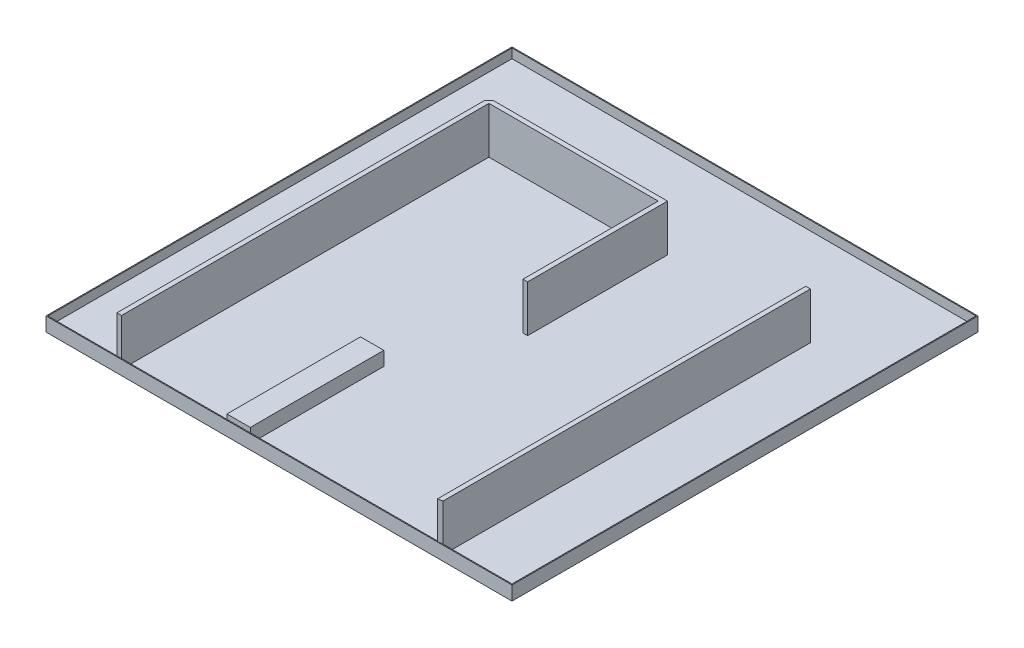
SolidWorks part; units mm, degrees
ref_plane "Front Plane" through (0, 0, 0) normal (0, 0, 1) x (1, 0, 0)
ref_plane "Top Plane" through (0, 0, 0) normal (0, 1, 0) x (1, 0, 0)
ref_plane "Right Plane" through (0, 0, 0) normal (1, 0, 0) x (0, 0, -1)
sketch "Sketch1" plane through (0, 0, 0) normal (0, 1, 0) x (1, 0, 0)
  line L1 (-5000, -5000) -> (5000, -5000)
  line L2 (-5000, -5000) -> (-5000, 5000)
  line L3 (-5000, 5000) -> (5000, 5000)
  line L4 (5000, -5000) -> (5000, 5000)
  line L5 (0, 5000) -> (0, -5000) construction
  line L6 (-5000, 0) -> (5000, 0) construction
  point P0 (0, 0)
  dimension "D1" = 10000
  dimension "D2" = 10000
extrude "Boss-Extrude1" add sketch "Sketch1" along normal blind 100
sketch "Sketch2" plane through (0, 100, 0) normal (0, 1, 0) x (1, 0, 0)
  line L1 (-5000, -5000) -> (5000, -5000)
  line L2 (-5000, -5000) -> (-5000, 5000)
  line L3 (-5000, 5000) -> (5000, 5000)
  line L4 (5000, -5000) -> (5000, 5000)
  line L5 (0, 5000) -> (0, -5000) construction
  line L6 (-5000, 0) -> (5000, 0) construction
  line L7 (-4980, -4980) -> (4980, -4980)
  line L8 (-4980, -4980) -> (-4980, 4980)
  line L9 (-4980, 4980) -> (4980, 4980)
  line L10 (4980, -4980) -> (4980, 4980)
  line L11 (0, 4980) -> (0, -4980) construction
  line L12 (-4980, 0) -> (4980, 0) construction
  point P0 (0, 0)
  point P4 (0, 0)
  dimension "D1" = 9960
  dimension "D2" = 9960
extrude "Boss-Extrude2" add sketch "Sketch2" along normal blind 200
sketch "Sketch5" plane through (0, 100, 0) normal (0, 1, 0) x (1, 0, 0)
  line L0 (3500, -4980) -> (3500, 2903.0481)
  line L1 (-4980, -4980) -> (4980, -4980) construction
  line L3 (3400, -5000) -> (3400, 2903.0481)
  line L4 (-5000, -5000) -> (5000, -5000) construction
  line L5 (5000, -5000) -> (5000, 5000) construction
  line L8 (334.6957, 3003.0481) -> (-3397.9365, 3003.0481)
  line L9 (-3497.9365, 2903.0481) -> (-3497.9365, -4980)
  line L10 (-3397.9365, 2903.0481) -> (-3397.9365, -4980)
  line L11 (234.6957, 2903.0481) -> (234.6957, 0)
  line L12 (334.6957, 2903.0481) -> (334.6957, 0)
  line L13 (234.6957, 0) -> (334.6957, 0)
  line L15 (3400, -5000) -> (3500, -4980)
  line L16 (-4980, -4980) -> (4980, -4980) construction
  line L17 (-3497.9365, -4980) -> (-3397.9365, -4980)
  line L20 (234.6957, 2903.0481) -> (-3397.9365, 2903.0481)
  line L23 (334.6957, 2903.0481) -> (334.6957, 3003.0481)
  line L24 (-3497.9365, 2903.0481) -> (-3397.9365, 3003.0481)
  line L25 (3400, 2903.0481) -> (3500, 2903.0481)
  dimension "D1" = 100
  dimension "D2" = 1500
  dimension "D4" = 100
  dimension "D5" = 100
extrude "Boss-Extrude3" add sketch "Sketch5" along normal blind 1000
sketch "Sketch6" plane through (0, 100, 0) normal (0, 1, 0) x (1, 0, 0)
  line L0 (-3397.9365, -4980) -> (3400, -4980) construction
  line L1 (-636.6432, -4980) -> (-1136.6432, -4980)
  line L2 (-636.6432, -4980) -> (-636.6432, -2114.5659)
  line L3 (-636.6432, -2114.5659) -> (-1136.6432, -2114.5659)
  line L4 (-1136.6432, -4980) -> (-1136.6432, -2114.5659)
  dimension "D1" = 500
extrude "Boss-Extrude4" add sketch "Sketch6" along normal blind 300
